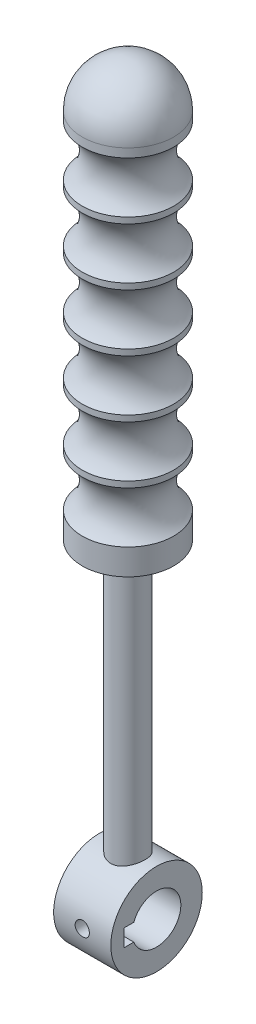
SolidWorks part; units mm, degrees
material "Brass"
ref_plane "Front Plane" through (0, 0, 0) normal (0, 0, 1) x (1, 0, 0)
ref_plane "Top Plane" through (0, 0, 0) normal (0, 1, 0) x (1, 0, 0)
ref_plane "Right Plane" through (0, 0, 0) normal (1, 0, 0) x (0, 0, -1)
ref_axis "Axis1" through (0, 132.7, 0) along (0, -1, 0)
sketch "Sketch1" plane through (0, 0, 0) normal (1, 0, 0) x (0, 0, -1)
  circle A0 centre (0, 0) radius 8
  dimension "D1" = 16
extrude "Shaft-Boss" add sketch "Sketch1" along normal mid plane 10
sketch "Sketch2" plane through (0, 0, 0) normal (0, 1, 0) x (1, 0, 0)
  circle A0 centre (0, 0) radius 3
  dimension "D1" = 6
extrude "Boss-Extrude2" add sketch "Sketch2" along normal blind 120
sketch "Sketch3" plane through (0, 0, 0) normal (1, 0, 0) x (0, 0, -1)
  line L0 (3, 120) -> (-3, 120) construction
  line L1 (0, 128) -> (0, 55)
  line L2 (0, 55) -> (-8, 55)
  line L3 (-8, 120) -> (-8, 55)
  arc A0 (0, 128) -> (-8, 120) centre (0, 120) ccw
  dimension "D2" = 8
  dimension "D1" = 65
revolve "Handle-Revolve" add sketch "Sketch3" angle 360 about L1
hole_wizard "Ø8.0 (8) Diameter Hole1" positions "Sketch5" profile "Sketch4" hole size "Ø8.0" standard "Ansi Metric"
sketch "Sketch5" plane through (5, 0, 0) normal (1, 0, 0) x (0, 0, -1)
  circle A0 centre (0, 0) radius 8 construction
  point P0 (0, 0)
sketch "Sketch4" plane through (5, 0, 0) normal (0, 1, 0) x (0, 0, -1)
  line L0 (0, 0) -> (0, 15.2537)
  line L1 (0, 15.2537) -> (4.25, 12.7)
  line L2 (4.25, 12.7) -> (4.25, 0)
  line L5 (4.25, 0) -> (0, 0)
  line L10 (0, 15.2537) -> (-4.25, 12.7) construction
  line L11 (0, -6.35) -> (0, 107.95) construction
  dimension "Hole Dia." = 8.5
  dimension "Hole Depth" = 12.7
  dimension "Drill Angle" = 118
sketch "Sketch6" plane through (5, 0, 0) normal (1, 0, 0) x (0, 0, -1)
  line L2 (-5.65, 1.5) -> (-2.65, 1.5)
  line L3 (-5.65, 1.5) -> (-5.65, -1.5)
  line L4 (-5.65, -1.5) -> (-2.65, -1.5)
  line L5 (-2.65, 1.5) -> (-2.65, -1.5)
  point P0 (-2.65, 0)
  dimension "D2" = 3
  dimension "D1" = 3
  dimension "D3" = 5.65
extrude "Cut-Keyway 3x3" cut sketch "Sketch6" against normal through all
hole_wizard "M3x0.5 Tapped Hole1" positions "Sketch8" profile "Sketch9" tap size "M3x0.5" standard "ANSI Metric"
sketch "Sketch8" plane through (0, 0, 0) normal (0, 0, 1) x (1, 0, 0)
  point P0 (0, 0)
cosmetic thread "Hole Thread1" parameters "D2"=3
sketch "Sketch9" plane through (0, 0, 0) normal (1, 0, 0) x (0, 1, 0)
  line L0 (0, 0) -> (0, 8)
  line L1 (0, 8) -> (1.25, 8)
  line L2 (1.25, 8) -> (1.25, 0)
  line L5 (1.25, 0) -> (0, 0)
  line L11 (0, -6.35) -> (0, 107.95) construction
  dimension "Thru Tap Drill Dia." = 2.5
  dimension "Thru Tap Drill Depth" = 8
sketch "Sketch7" plane through (0, 0, 0) normal (1, 0, 0) x (0, 0, -1)
  line L0 (0, 8.8) -> (0, -8.8) construction
  line L1 (-8, 120) -> (8, 120) construction
  circle A0 centre (-12, 114) radius 6
  dimension "D1" = 12
  dimension "D2" = 12
  dimension "D3" = 6
revolve "Cut-Revolve1" cut sketch "Sketch7" angle 360 about axis through (0, 132.7, 0) along (0, -1, 0)
pattern_linear "LPattern1" count 6 spacing 10 along (0, -1, 0) of "Cut-Revolve1"
